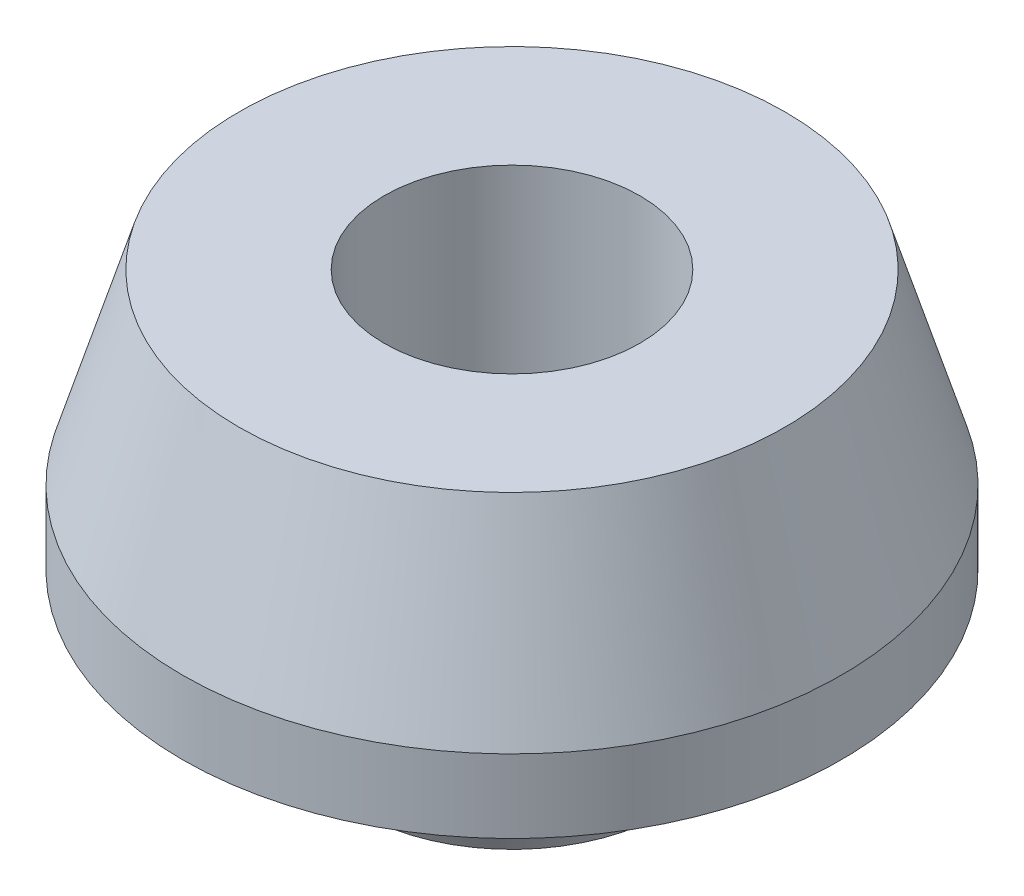
SolidWorks part; units mm, degrees
material "Rubber"
ref_plane "Front Plane" through (0, 0, 0) normal (0, 0, 1) x (1, 0, 0)
ref_plane "Top Plane" through (0, 0, 0) normal (0, 1, 0) x (1, 0, 0)
ref_plane "Right Plane" through (0, 0, 0) normal (1, 0, 0) x (0, 0, -1)
sketch "Sketch1" plane through (0, 0, 0) normal (0, 0, 1) x (1, 0, 0)
  line L0 (4.8, 0) -> (5.8, 0)
  line L1 (5.8, 0) -> (7.6199, 5)
  line L2 (7.6199, 5) -> (12.3699, 5)
  line L3 (12.3699, 5) -> (12.3699, 7.75)
  line L4 (12.3699, 7.75) -> (10.25, 14.75)
  line L5 (10.25, 14.75) -> (4.8, 14.75)
  line L6 (4.8, 14.75) -> (4.8, 0)
  line L7 (0, 17.8514) -> (0, -4.7272) construction
  dimension "D1" = 14.75
  dimension "D2" = 4.8
  dimension "D3" = 2.75
  dimension "D4" = 9.75
  dimension "D5" = 4.75
  dimension "D6" = 110
  dimension "D7" = 5.45
  dimension "D8" = 1
revolve "Revolve1" add sketch "Sketch1" angle 360 about L7
